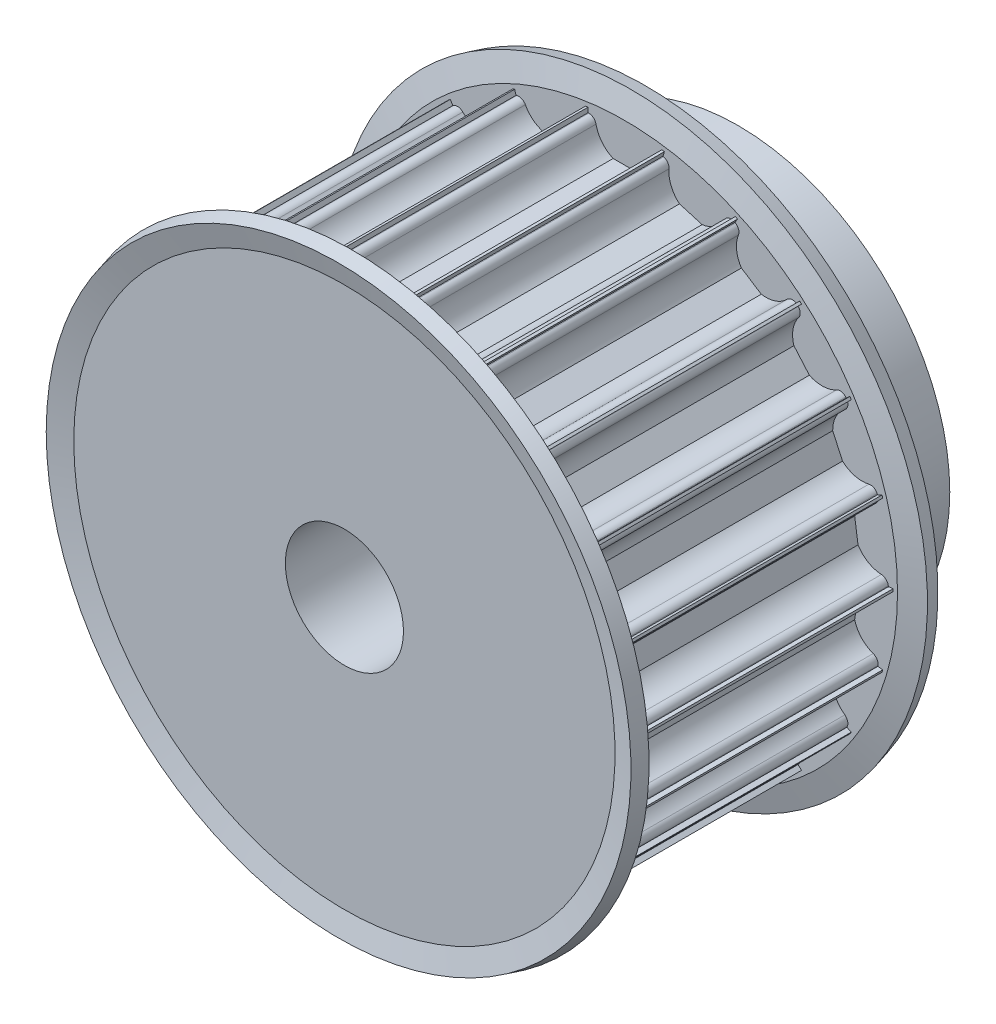
SolidWorks part; units mm, degrees
ref_plane "Front Plane" through (0, 0, 0) normal (0, 0, 1) x (1, 0, 0)
ref_plane "Top Plane" through (0, 0, 0) normal (0, 1, 0) x (1, 0, 0)
ref_plane "Right Plane" through (0, 0, 0) normal (1, 0, 0) x (0, 0, -1)
sketch "Sketch2" plane through (0, 0, 0) normal (1, 0, 0) x (0, 0, -1)
  line L0 (0, 0) -> (26.2549, 0) construction
  line L1 (0, 6) -> (40, 6)
  line L2 (40, 6) -> (40, 21.5)
  line L3 (40, 21.5) -> (30, 21.5)
  line L4 (30, 21.5) -> (30, 27.25)
  line L5 (30, 27.25) -> (0, 27.25)
  line L6 (0, 27.25) -> (0, 6)
  dimension "D1" = 27.25
  dimension "D2" = 6
  dimension "D3" = 30
  dimension "D4" = 10
  dimension "D5" = 15.5
revolve "Revolve1" add sketch "Sketch2" angle 360 about L0
sketch "Sketch3" plane through (0, 0, 0) normal (0, 0, 1) x (1, 0, 0)
  line L0 (-3.6742, 26.5) -> (-3.75, 26.5)
  line L1 (-3.75, 26.5) -> (-3.75, 28.5)
  line L2 (-3.75, 28.5) -> (3.75, 28.5)
  line L3 (3.75, 28.5) -> (3.75, 26.5)
  line L4 (3.75, 26.5) -> (3.6742, 26.5)
  line L5 (-1.199, 23.75) -> (1.199, 23.75)
  arc A0 (2.9394, 25.9) -> (1.199, 23.75) centre (0, 26.5) cw
  arc A1 (2.9394, 25.9) -> (3.6742, 26.5) centre (3.6742, 25.75) cw
  arc A2 (-2.9394, 25.9) -> (-3.6742, 26.5) centre (-3.6742, 25.75) ccw
  arc A3 (-1.199, 23.75) -> (-2.9394, 25.9) centre (0, 26.5) cw
  point P10 (0, 28.5)
  point P13 (3, 26.5)
  point P16 (-3, 26.5)
  dimension "D1" = 3
  dimension "D5" = 0.75
  dimension "D2" = 26.5
  dimension "D3" = 2
  dimension "D4" = 7.5
  dimension "D6" = 2.75
extrude "Cut-Extrude1" cut sketch "Sketch3" against normal up to next
pattern_circular "CirPattern1" count 22 over 360 about axis through (0, 0, 0) along (0, 0, 1) of "Cut-Extrude1"
sketch "Sketch4" plane through (0, 0, 0) normal (1, 0, 0) x (0, 0, -1)
  line L0 (15, 26.9539) -> (15, 14.3507) construction
  line L1 (30, 26.9539) -> (0, 26.9539) construction
  line L2 (30, 14.3507) -> (0, 14.3507) construction
  line L3 (30, 21.5) -> (30, 27.4925)
  line L4 (30, 27.4925) -> (30.592, 29.7018)
  line L5 (30.592, 29.7018) -> (29.1431, 30.09)
  line L6 (29.1431, 30.09) -> (28.5, 27.69)
  line L9 (28.5, 21.5) -> (30, 21.5)
  line L10 (28.5, 27.69) -> (28.5, 21.5)
  line L11 (40, 21.5) -> (30, 21.5) construction
  line L12 (1.5, 21.5) -> (0, 21.5)
  line L13 (1.5, 27.69) -> (1.5, 21.5)
  line L14 (-0.592, 29.7018) -> (0.8569, 30.09)
  line L15 (0.8569, 30.09) -> (1.5, 27.69)
  line L16 (0, 27.4925) -> (-0.592, 29.7018)
  line L17 (0, 21.5) -> (0, 27.4925)
  line L18 (0, 0) -> (-7.8265, 0) construction
  dimension "D1" = 15
  dimension "D2" = 1.5
  dimension "D3" = 6.19
  dimension "D4" = 2.4
revolve "Revolve2" add sketch "Sketch4" angle 360 about L18
